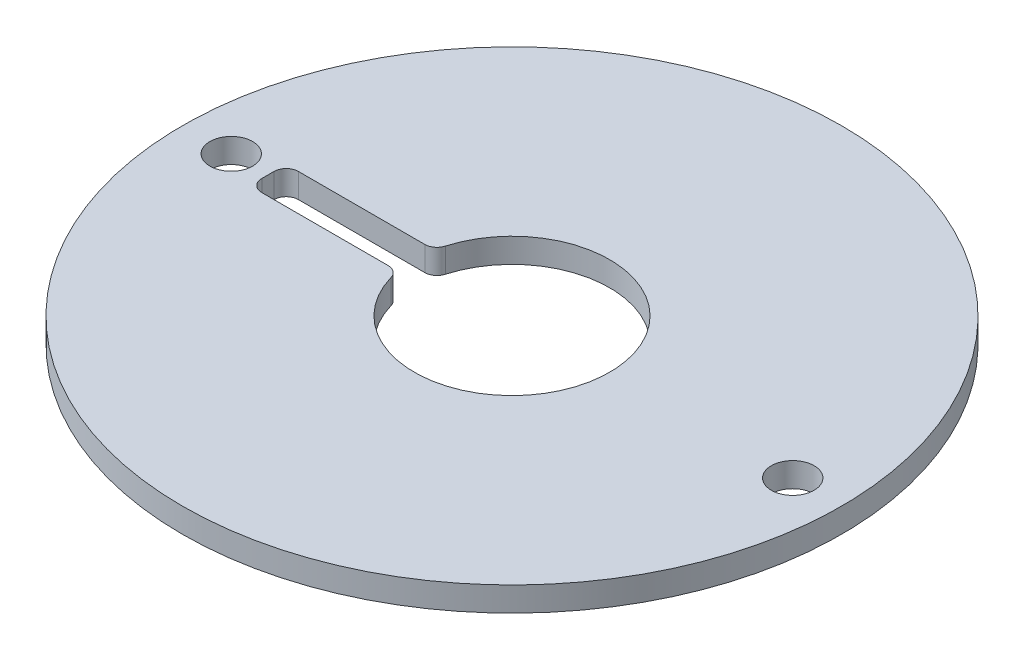
SolidWorks part; units mm, degrees
ref_plane "Front Plane" through (0, 0, 0) normal (0, 0, 1) x (1, 0, 0)
ref_plane "Top Plane" through (0, 0, 0) normal (0, 1, 0) x (1, 0, 0)
ref_plane "Right Plane" through (0, 0, 0) normal (1, 0, 0) x (0, 0, -1)
sketch "Sketch1" plane through (0, 0, 0) normal (0, 1, 0) x (1, 0, 0)
  line L0 (-25, 0) -> (25, 0) construction
  circle A0 centre (0, 0) radius 8
  circle A1 centre (0, 0) radius 27
  circle A2 centre (0, 0) radius 25 construction
  circle A3 centre (-23, 0) radius 1.75
  circle A4 centre (23, 0) radius 1.75
  dimension "D1" = 16
  dimension "D2" = 54
  dimension "D3" = 50
  dimension "D4" = 3.5
  dimension "D6" = 3.5
  dimension "D5" = 2
  dimension "D7" = 2
extrude "Boss-Extrude1" add sketch "Sketch1" along normal blind 2
sketch "Sketch2" plane through (0, 2, 0) normal (0, 1, 0) x (1, 0, 0)
  line L0 (-27, 0) -> (27, 0) construction
  line L1 (-20, 1.5) -> (-5, 1.5)
  line L2 (-20, 1.5) -> (-20, -1.5)
  line L3 (-20, -1.5) -> (-5, -1.5)
  line L4 (-5, 1.5) -> (-5, -1.5)
  circle A0 centre (0, 0) radius 27 construction
  point P9 (-5, 0)
  dimension "D1" = 3
  dimension "D2" = 15
  dimension "D3" = 7
extrude "Cut-Extrude1" cut sketch "Sketch2" against normal through all
fillet "Fillet1" radius 1 4 edges at (-20, 1, 1.5) (-20, 1, -1.5) (-7.8581, 1, 1.5) (-7.8581, 1, -1.5)
